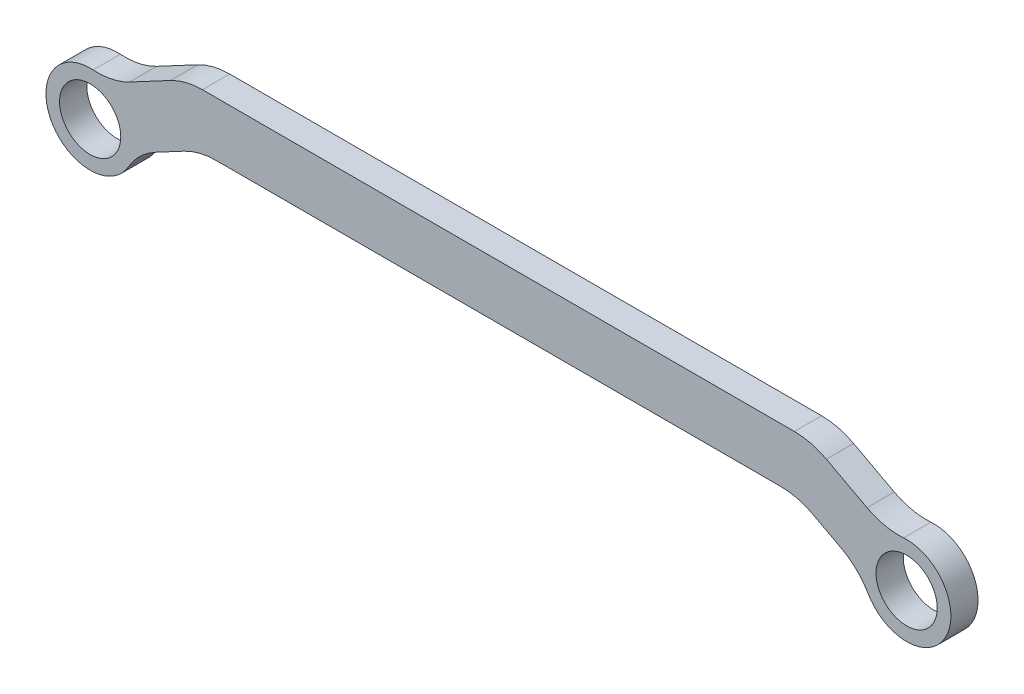
SolidWorks part; units mm, degrees
ref_plane "Front Plane" through (0, 0, 0) normal (0, 0, 1) x (1, 0, 0)
ref_plane "Top Plane" through (0, 0, 0) normal (0, 1, 0) x (1, 0, 0)
ref_plane "Right Plane" through (0, 0, 0) normal (1, 0, 0) x (0, 0, -1)
sketch "Sketch1" plane through (0, 0, 0) normal (0, 0, 1) x (1, 0, 0)
  line L0 (0, 0) -> (120, 0) construction
  line L1 (0, 0) -> (15, 8) construction
  line L3 (15, 8) -> (105, 8) construction
  line L5 (105, 8) -> (120, 0) construction
  line L6 (6.4031, -1.1184) -> (16, 4)
  line L7 (16, 4) -> (104, 4)
  line L8 (104, 4) -> (113.5969, -1.1184)
  line L9 (2.6384, 5.9405) -> (14, 12)
  line L10 (14, 12) -> (106, 12)
  line L11 (106, 12) -> (117.3616, 5.9405)
  line L12 (-1.8824, 3.5294) -> (14, 12) construction
  line L13 (1.8824, -3.5294) -> (16, 4) construction
  line L15 (106, 12) -> (121.8824, 3.5294) construction
  line L17 (104, 4) -> (118.1176, -3.5294) construction
  circle A0 centre (0, 0) radius 4.5
  circle A1 centre (0, 0) radius 6.5
  circle A2 centre (120, 0) radius 4.5
  circle A3 centre (120, 0) radius 6.5
  dimension "D1" = 9
  dimension "D2" = 13
  dimension "D4" = 9
  dimension "D5" = 13
  dimension "D3" = 120
  dimension "D6" = 8
  dimension "D7" = 90
  dimension "D8" = 4
  dimension "D9" = 4
extrude "Boss-Extrude1" add sketch "Sketch1" along normal blind 4 contours A3 L11 L10 L9 A1 L6 L7 L8 | A1 A0 | A3 A2
fillet "Fillet1" radius 10 8 edges at (113.5969, -1.1184, 2) (117.3616, 5.9405, 2) (104, 4, 2) (106, 12, 2) (16, 4, 2) (14, 12, 2) (6.4031, -1.1184, 2) (2.6384, 5.9405, 2)
